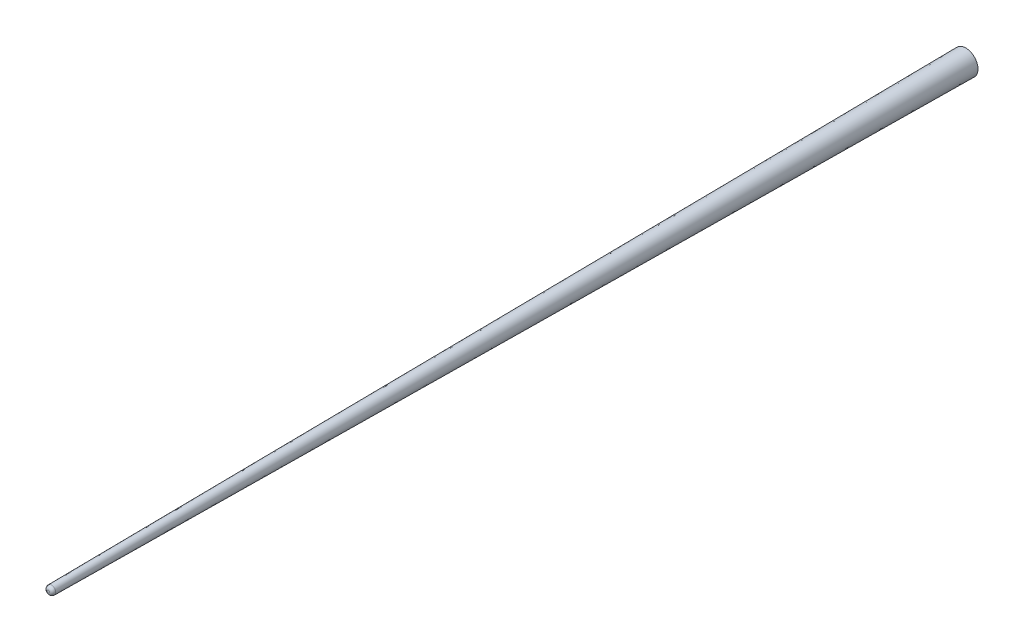
SolidWorks part; units mm, degrees
ref_plane "Front Plane" through (0, 0, 0) normal (0, 0, 1) x (1, 0, 0)
ref_plane "Top Plane" through (0, 0, 0) normal (0, 1, 0) x (1, 0, 0)
ref_plane "Right Plane" through (0, 0, 0) normal (1, 0, 0) x (0, 0, -1)
sketch "Sketch1" plane through (0, 0, 0) normal (0, 0, 1) x (1, 0, 0)
  circle A0 centre (0, 0) radius 0.508
extrude "Boss-Extrude1" add sketch "Sketch1" along normal blind 38.1 draft 0.5
fillet "Fillet2" radius 0.127 1 edges at (0.1755, 0, 38.1)
